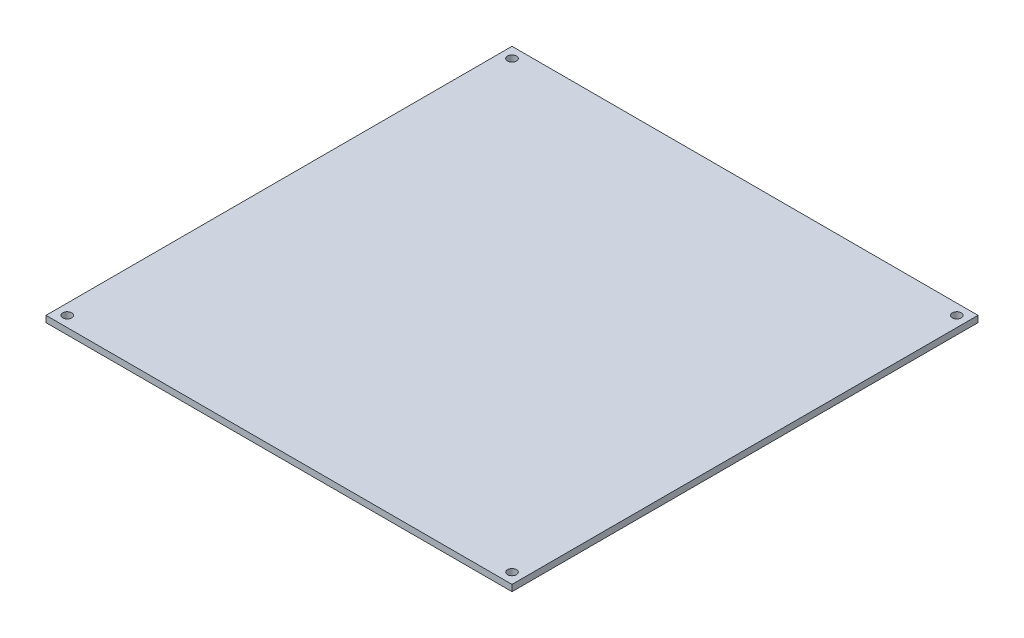
SolidWorks part; units mm, degrees
ref_plane "Front Plane" through (0, 0, 0) normal (0, 0, 1) x (1, 0, 0)
ref_plane "Top Plane" through (0, 0, 0) normal (0, 1, 0) x (1, 0, 0)
ref_plane "Right Plane" through (0, 0, 0) normal (1, 0, 0) x (0, 0, -1)
sketch "Sketch1" plane through (0, 0, 0) normal (0, 1, 0) x (1, 0, 0)
  line L1 (-110, -110) -> (110, -110)
  line L2 (-110, -110) -> (-110, 110)
  line L3 (-110, 110) -> (110, 110)
  line L4 (110, -110) -> (110, 110)
  line L5 (-110, -110) -> (110, 110) construction
  line L6 (-110, 110) -> (110, -110) construction
  circle A0 centre (-105, 105) radius 2.1
  circle A1 centre (105, 105) radius 2.1
  circle A2 centre (105, -105) radius 2.1
  circle A3 centre (-105, -105) radius 2.1
  point P0 (0, 0)
  dimension "D2" = 5
  dimension "D1" = 220
  dimension "D4" = 2
  dimension "D3" = 2
extrude "Boss-Extrude1" add sketch "Sketch1" along normal blind 3
